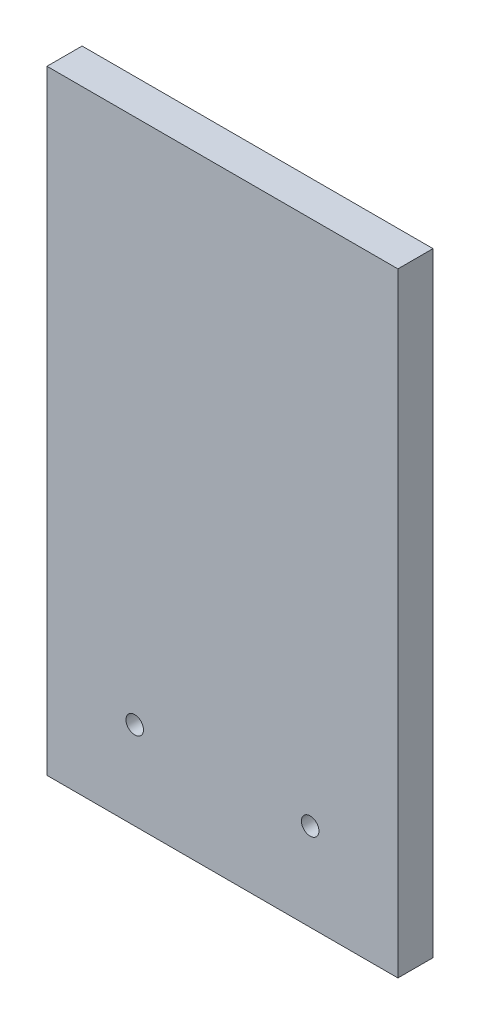
SolidWorks part; units mm, degrees
material "Faia"
ref_plane "Plano frontal" through (0, 0, 0) normal (0, 0, 1) x (1, 0, 0)
ref_plane "Plano superior" through (0, 0, 0) normal (0, 1, 0) x (1, 0, 0)
ref_plane "Plano direito" through (0, 0, 0) normal (1, 0, 0) x (0, 0, -1)
sketch "Esboço1" plane through (0, 0, 0) normal (0, 0, 1) x (1, 0, 0)
  line L0 (-50, -87.5) -> (50, 87.5) construction
  line L1 (50, 87.5) -> (-50, 87.5)
  line L2 (50, 87.5) -> (50, -87.5)
  line L3 (50, -87.5) -> (-50, -87.5)
  line L4 (-50, 87.5) -> (-50, -87.5)
  point P4 (0, 0)
  dimension "D1" = 100
  dimension "D2" = 175
extrude "Ressalto-extrusão1" add sketch "Esboço1" along normal blind 10
sketch "Esboço2" plane through (0, 0, 10) normal (0, 0, 1) x (1, 0, 0)
  line L0 (-50, 87.5) -> (0, 87.5) construction
  line L1 (50, 87.5) -> (-50, 87.5) construction
  line L2 (0, 87.5) -> (50, 87.5) construction
  line L3 (-25, 87.5) -> (-25, -62.5) construction
  line L4 (-25, -62.5) -> (25, -62.5) construction
  line L5 (25, -62.5) -> (25, 87.5) construction
  circle A0 centre (-25, -62.5) radius 2.5
  circle A1 centre (25, -62.5) radius 2.5
  dimension "D1" = 5
  dimension "D2" = 150
extrude "Corte-extrusão1" cut sketch "Esboço2" against normal through all contours A0 | A1
